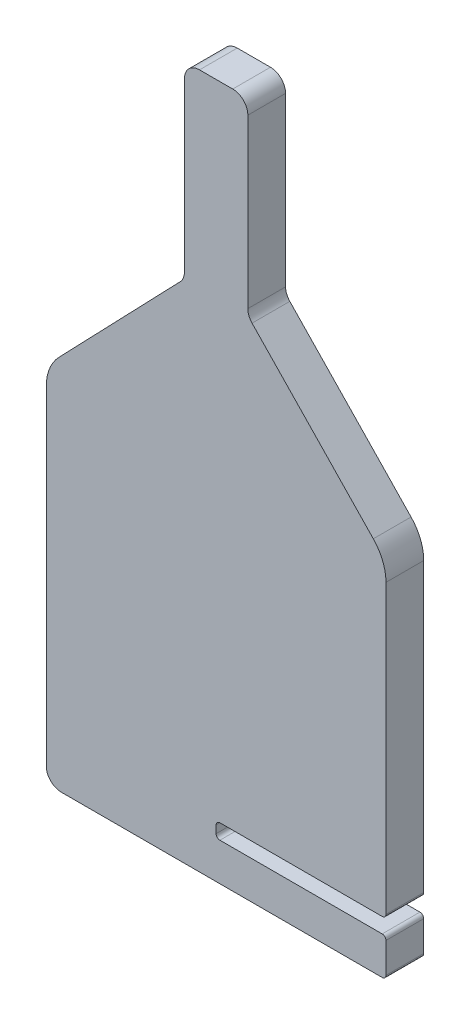
SolidWorks part; units mm, degrees
ref_plane "Alzado" through (0, 0, 0) normal (0, 0, 1) x (1, 0, 0)
ref_plane "Planta" through (0, 0, 0) normal (0, 1, 0) x (1, 0, 0)
ref_plane "Vista lateral" through (0, 0, 0) normal (1, 0, 0) x (0, 0, -1)
sketch "Croquis1" plane through (0, 0, 0) normal (0, 0, 1) x (1, 0, 0)
  line L0 (-4.2, 20) -> (-22.5, 0.9719)
  line L1 (-4.2, 45) -> (4.2, 45)
  line L2 (-22.5, 0.9719) -> (-22.5, -47.0281)
  line L3 (-22.5, -47.0281) -> (22.5, -47.0281)
  line L4 (22.5, 0.9719) -> (22.5, -47.0281)
  line L5 (-4.2, 45) -> (4.2, 45)
  line L6 (-4.2, 45) -> (-4.2, 20)
  line L8 (4.2, 45) -> (4.2, 19.999)
  line L9 (4.2, 19.999) -> (22.5, 0.9719)
  line L10 (0, 72.8664) -> (0, -82.626) construction
  dimension "D1" = 45
  dimension "D2" = 25
  dimension "D3" = 4.2
  dimension "D4" = 22.5
  dimension "D5" = 45
  dimension "D6" = 4.2
  dimension "D7" = 26.3993
  dimension "D8" = 26.4
  dimension "D9" = 48
  dimension "D10" = 48
extrude "Saliente-Extruir1" add sketch "Croquis1" along normal blind 5 contours L6 L0 L2 L3 L4 L9 L8 L1
sketch "Croquis3" plane through (0, 0, 5) normal (0, 0, 1) x (1, 0, 0)
  line L0 (22.5, 0.9719) -> (22.5, -47.0281) construction
  line L1 (22.5, -40.0281) -> (0, -40.0281)
  line L2 (22.5, -40.0281) -> (22.5, -42.0281)
  line L3 (22.5, -42.0281) -> (0, -42.0281)
  line L4 (0, -40.0281) -> (0, -42.0281)
  line L5 (-22.5, -47.0281) -> (22.5, -47.0281) construction
  dimension "D1" = 2
  dimension "D2" = 5
  dimension "D3" = 22.5
extrude "Cortar-Extruir2" cut sketch "Croquis3" against normal up to surface (5 mm away) up to face at (0, 4.7358, 0)
fillet "Redondeo1" radius 2 5 edges at (-22.5, -47.0281, 2.5) (-4.2, 20, 2.5) (-4.2, 45, 2.5) (4.2, 19.999, 2.5) (4.2, 45, 2.5)
fillet "Redondeo2" radius 6 2 edges at (-22.5, 0.9719, 2.5) (22.5, 0.9719, 2.5)
fillet "Redondeo3" radius 0.5 5 edges at (22.5, -47.0281, 2.5) (0, -42.0281, 2.5) (0, -40.0281, 2.5) (22.5, -40.0281, 2.5) (22.5, -42.0281, 2.5)
